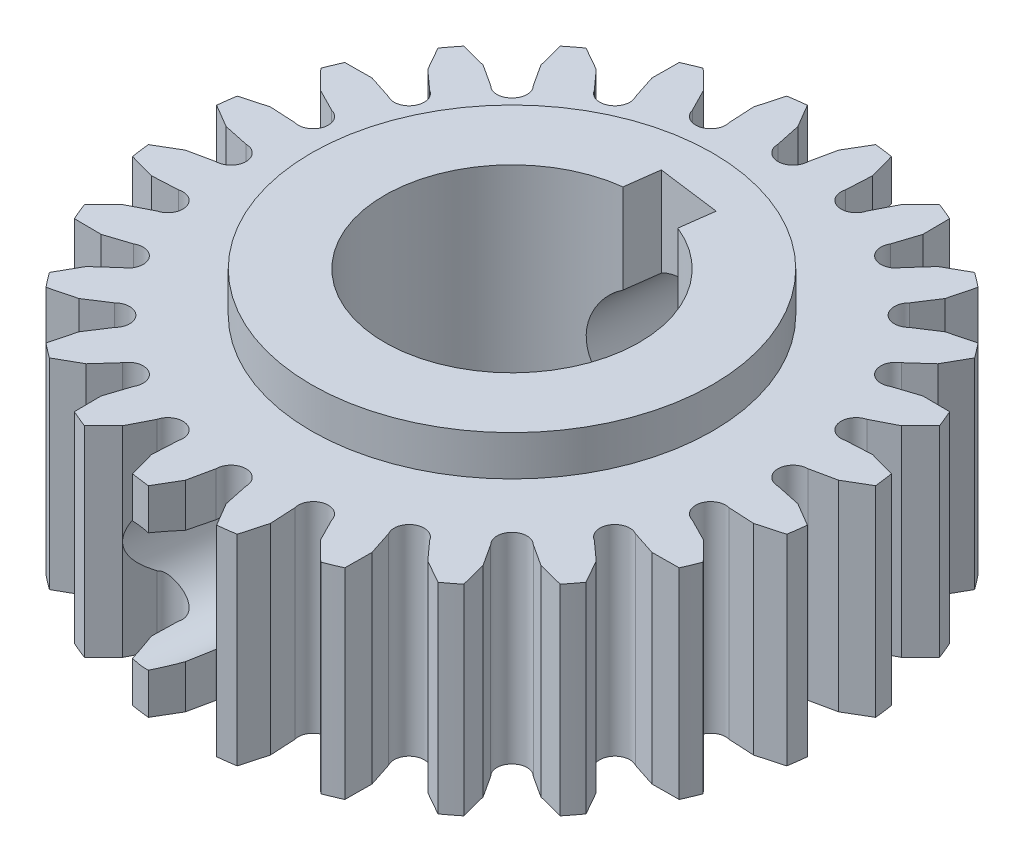
SolidWorks part; units mm, degrees
ref_plane "Front Plane" through (0, 0, 0) normal (0, 0, 1) x (1, 0, 0)
ref_plane "Top Plane" through (0, 0, 0) normal (0, 1, 0) x (1, 0, 0)
ref_plane "Right Plane" through (0, 0, 0) normal (1, 0, 0) x (0, 0, -1)
sketch "Sketch2" plane through (0, 0, 0) normal (0, 1, 0) x (1, 0, 0)
  line L0 (0, 8.255) -> (0, -8.255) construction
  line L1 (-8.255, 0) -> (8.255, 0) construction
  circle A0 centre (0, 0) radius 8.255
  circle A1 centre (0, 0) radius 6.6275 construction
  arc A2 (-0.375, 7.0025) -> (0.375, 7.0025) centre (0, 7.0025) ccw
  circle A3 centre (0, 0) radius 7.3775 construction
  spline S0 degree 2 poles (-0.375, 7.0025) (-0.5021, 7.6737) (-0.9758, 8.1971) knots 0 0 0 1 1 1
  spline S1 degree 2 poles (0.375, 7.0025) (0.5021, 7.6737) (0.9758, 8.1971) knots 0 0 0 1 1 1
  point P13 (-0.4718, 7.3624)
  dimension "D1" = 16.51
  dimension "D2" = 13.255
  dimension "D3" = 0.75
extrude "Boss-Extrude2" add sketch "Sketch2" along normal blind 5 contours S1 A2 S0 A0 | A2 S1 A0 S0
sketch "Sketch3" plane through (0, 5, 0) normal (0, 1, 0) x (1, 0, 0)
  line L0 (0, 8.255) -> (0, 0) construction
  line L1 (-0.375, 7.0025) -> (-0.5088, 7.6316)
  line L2 (-0.5088, 7.6316) -> (-0.85, 8.2111)
  line L3 (0.375, 7.0025) -> (0.5088, 7.6316)
  line L4 (0.5088, 7.6316) -> (0.85, 8.2111)
  arc A0 (-0.375, 7.0025) -> (0.375, 7.0025) centre (0, 7.0025) ccw construction
  arc A3 (-0.375, 7.0025) -> (0.375, 7.0025) centre (0, 7.0025) ccw
  circle A6 centre (0, 0) radius 8.255 construction
  arc A7 (-0.85, 8.2111) -> (0.85, 8.2111) centre (0, 0) cw
  dimension "D1" = 0.85
extrude "Cut-Extrude2" cut sketch "Sketch3" against normal through all
pattern_circular "CirPattern1" count 24 over 360 about axis through (0, 0, 0) along (0, 1, 0) of "Cut-Extrude2"
sketch "Sketch4" plane through (0, 5, 0) normal (0, 1, 0) x (1, 0, 0)
  circle A0 centre (0, 0) radius 5
  dimension "D1" = 10
extrude "Boss-Extrude3" add sketch "Sketch4" along normal blind 1
sketch "Sketch5" plane through (0, 6, 0) normal (0, 1, 0) x (1, 0, 0)
  circle A0 centre (0, 0) radius 3.175
  dimension "D1" = 6.35
extrude "Cut-Extrude3" cut sketch "Sketch5" against normal through all
sketch "Sketch6" plane through (0, 6, 0) normal (0, 1, 0) x (1, 0, 0)
  line L0 (-1.5215, -11.5566) -> (1.5215, 11.5566) construction
  line L1 (0, -11.3334) -> (0, 11.3334) construction
  line L2 (-2.3726, -11.9425) -> (0.7716, 11.9401) construction
  line L3 (-0.7992, -12.1497) -> (2.345, 11.733) construction
  line L4 (-0.4106, 2.9606) -> (-0.2744, 3.995)
  line L5 (-0.4106, 2.9606) -> (1.1629, 2.7535)
  line L6 (-0.2744, 3.995) -> (1.299, 3.7878)
  line L7 (1.1629, 2.7535) -> (1.299, 3.7878)
  circle A1 centre (0, 0) radius 3.175 construction
  point P6 (0, 0)
  point P12 (0, 0)
  point P15 (-0.8005, -0.0012)
  dimension "D1" = 7.5
  dimension "D2" = 0.7935
  dimension "D3" = 0.75
extrude "Cut-Extrude4" cut sketch "Sketch6" against normal through all both and the other way through all
ref_plane "Plane1" through (0, 2.5, 0) normal (0, 1, 0) x (1, 0, 0)
sketch "Sketch7" plane through (0, 2.5, 0) normal (0, 1, 0) x (1, 0, 0)
  line L0 (-1.4577, -11.072) -> (1.4577, 11.072)
  line L1 (0, -12.1386) -> (0, 12.1386) construction
  line L2 (-0.0553, 11.072) -> (-2.9706, -11.072)
  line L3 (-2.9706, -11.072) -> (-1.4577, -11.072)
  line L4 (-0.0553, 11.072) -> (1.4577, 11.072)
  point P5 (0, 0)
  point P11 (0, 0)
  dimension "D1" = 7.5
  dimension "D2" = 1.5
revolve "Cut-Revolve1" cut sketch "Sketch7" angle 360 about L0
